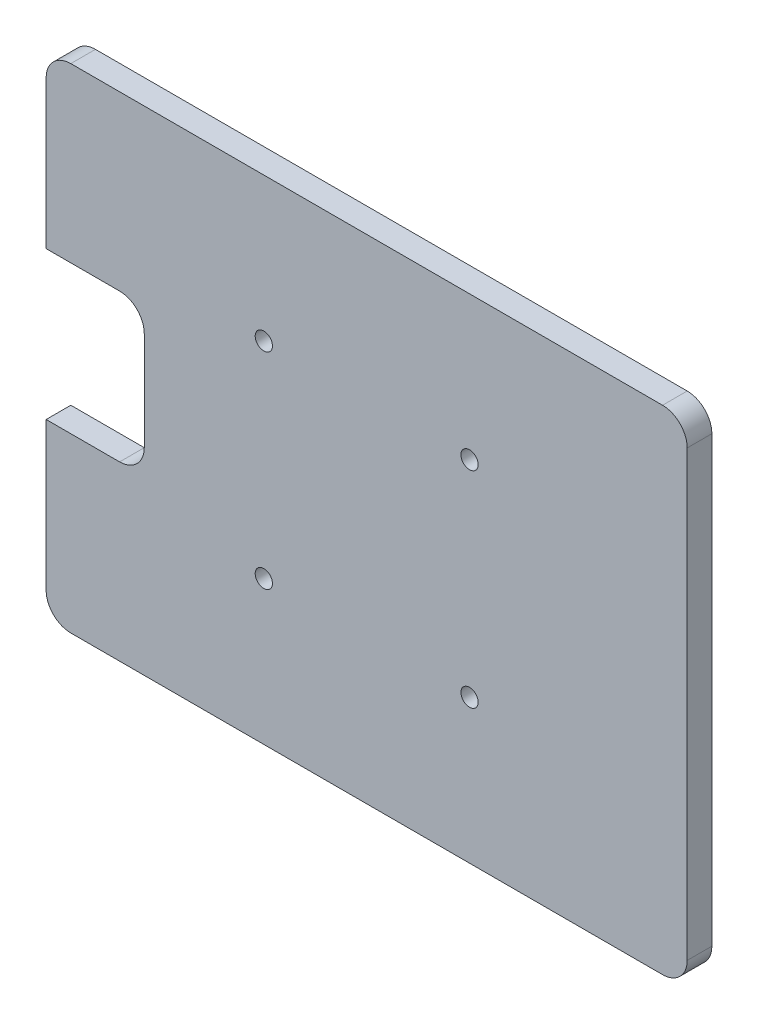
SolidWorks part; units mm, degrees
ref_plane "Front" through (0, 0, 0) normal (0, 0, 1) x (1, 0, 0)
ref_plane "Top" through (0, 0, 0) normal (0, 1, 0) x (1, 0, 0)
ref_plane "Right" through (0, 0, 0) normal (1, 0, 0) x (0, 0, -1)
sketch "Esquisse1" plane through (0, 0, 0) normal (0, 0, 1) x (1, 0, 0)
  line L1 (-76.0081, 52.6815) -> (53.9919, 52.6815)
  line L2 (-76.0081, 52.6815) -> (-76.0081, -47.3185)
  line L3 (-76.0081, -47.3185) -> (53.9919, -47.3185)
  line L4 (53.9919, 52.6815) -> (53.9919, -47.3185)
  dimension "D1" = 130
  dimension "D2" = 100
extrude "Boss.-Extru.1" add sketch "Esquisse1" along normal blind 5
sketch "Esquisse2" plane through (0, 0, 5) normal (0, 0, 1) x (1, 0, 0)
  circle A0 centre (-11.0081, 2.6815) radius 82.0061
  circle A1 centre (-11.0081, 2.6815) radius 29.5
  circle A3 centre (9.8516, -18.1782) radius 1.75
  circle A4 centre (-31.8677, -18.1782) radius 1.75
  circle A5 centre (-31.8677, 23.5411) radius 1.75
  circle A6 centre (9.8516, 23.5411) radius 1.75
  point P17 (-11.0081, 2.6815)
  dimension "D1" = 4
extrude "Enlèv. mat.-Extru.1" cut sketch "Esquisse2" against normal blind 10 contours A1 A5 | A1 A5 | A1 A6 | A1 A6 | A1 A3 | A1 A3 | A1 A4 | A1 A4
ref_plane "Plan1" through (-76.0081, 52.6815, 5) normal (0, -1, 0) x (-1, 0, 0)
sketch "Esquisse4" plane through (0, 0, 5) normal (0, 0, 1) x (1, 0, 0)
  line L0 (-76.0081, 52.6815) -> (-76.0081, -47.3185) construction
  line L1 (-76.0081, 17.6815) -> (-56.1075, 17.6815)
  line L2 (-76.0081, 17.6815) -> (-76.0081, -12.3185)
  line L3 (-76.0081, -12.3185) -> (-56.1075, -12.3185)
  line L4 (-56.1075, 17.6815) -> (-56.1075, -12.3185)
  line L5 (53.9919, 52.6815) -> (-76.0081, 52.6815) construction
  dimension "D1" = 30
  dimension "D2" = 35
extrude "Enlèv. mat.-Extru.2" cut sketch "Esquisse4" against normal blind 10
fillet "Congé1" radius 5 6 edges at (53.9919, -47.3185, 2.5) (53.9919, 52.6815, 2.5) (-76.0081, 52.6815, 2.5) (-56.1075, -12.3185, 2.5) (-56.1075, 17.6815, 2.5) (-76.0081, -47.3185, 2.5)
